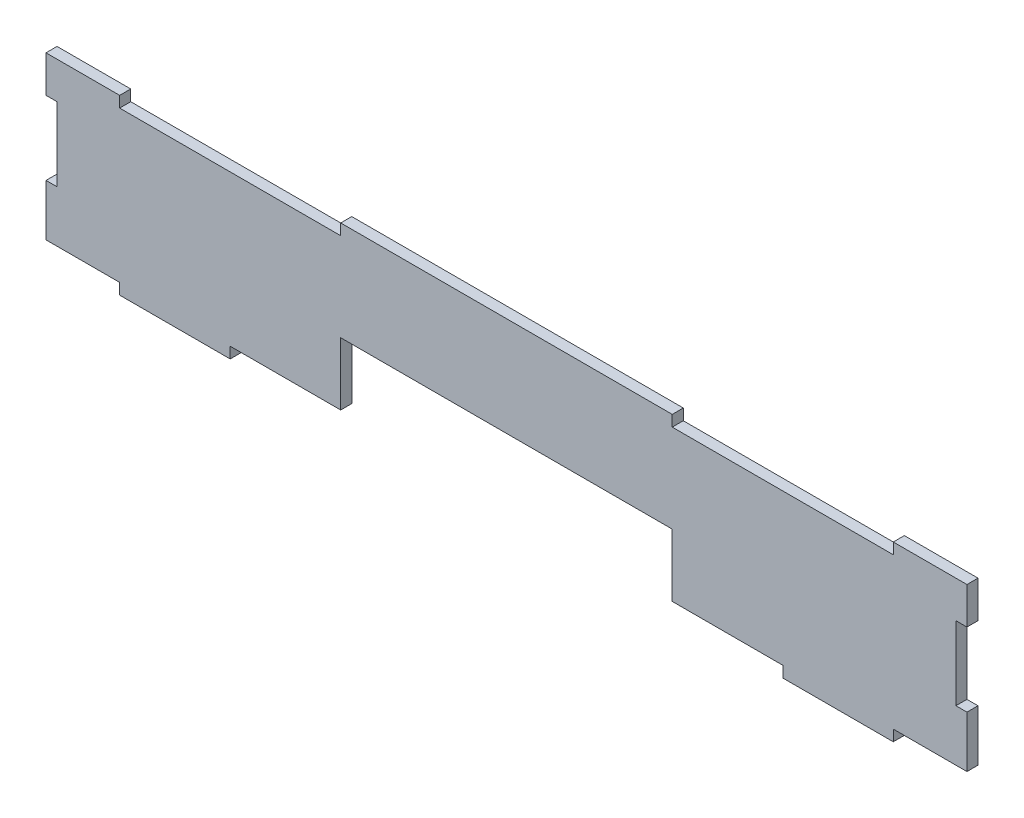
SolidWorks part; units mm, degrees
ref_plane "Front Plane" through (0, 0, 0) normal (0, 0, 1) x (1, 0, 0)
ref_plane "Top Plane" through (0, 0, 0) normal (0, 1, 0) x (1, 0, 0)
ref_plane "Right Plane" through (0, 0, 0) normal (1, 0, 0) x (0, 0, -1)
sketch "Sketch1" plane through (0, 0, 0) normal (0, 0, 1) x (1, 0, 0)
  line L1 (0, 0) -> (250, 0)
  line L2 (0, 0) -> (0, 46.98)
  line L3 (0, 46.98) -> (250, 46.98)
  line L4 (250, 0) -> (250, 46.98)
  dimension "D1" = 250
  dimension "D2" = 46.98
extrude "Boss-Extrude1" add sketch "Sketch1" along normal blind 3
sketch "Sketch2" plane through (0, 0, 3) normal (0, 0, 1) x (1, 0, 0)
  line L0 (250, 0) -> (250, 46.98) construction
  line L1 (250, 36.98) -> (247, 36.98)
  line L2 (250, 36.98) -> (250, 16.98)
  line L3 (250, 16.98) -> (247, 16.98)
  line L4 (247, 36.98) -> (247, 16.98)
  line L5 (0, 46.98) -> (0, 0) construction
  line L6 (0, 36.98) -> (3, 36.98)
  line L7 (0, 36.98) -> (0, 16.98)
  line L8 (0, 16.98) -> (3, 16.98)
  line L9 (3, 36.98) -> (3, 16.98)
  line L10 (250, 46.98) -> (0, 46.98) construction
  dimension "D1" = 3
  dimension "D2" = 3
  dimension "D3" = 20
  dimension "D4" = 20
  dimension "D5" = 10
  dimension "D6" = 10
extrude "Cut-Extrude1" cut sketch "Sketch2" against normal through all
sketch "Sketch3" plane through (0, 0, 3) normal (0, 0, 1) x (1, 0, 0)
  line L0 (250, 46.98) -> (0, 46.98) construction
  line L1 (20, 46.98) -> (80, 46.98)
  line L2 (20, 46.98) -> (20, 43.98)
  line L3 (20, 43.98) -> (80, 43.98)
  line L4 (80, 46.98) -> (80, 43.98)
  line L5 (0, 46.98) -> (0, 36.98) construction
  line L6 (230, 46.98) -> (170, 46.98)
  line L7 (230, 46.98) -> (230, 43.98)
  line L8 (230, 43.98) -> (170, 43.98)
  line L9 (170, 46.98) -> (170, 43.98)
  line L10 (250, 36.98) -> (250, 46.98) construction
  point P12 (250, 41.98)
  dimension "D1" = 60
  dimension "D2" = 60
  dimension "D3" = 20
  dimension "D4" = 20
  dimension "D5" = 3
  dimension "D6" = 3
extrude "Cut-Extrude2" cut sketch "Sketch3" against normal through all
sketch "Sketch4" plane through (0, 0, 0) normal (0, 0, -1) x (-1, 0, 0)
  line L0 (0, 0) -> (-250, 0) construction
  line L1 (-80, 0) -> (-170, 0)
  line L2 (-80, 0) -> (-80, 20)
  line L3 (-80, 20) -> (-170, 20)
  line L4 (-170, 0) -> (-170, 20)
  line L5 (0, 16.98) -> (0, 0) construction
  dimension "D1" = 20
  dimension "D2" = 90
  dimension "D3" = 80
extrude "Cut-Extrude3" cut sketch "Sketch4" against normal up to next
sketch "Sketch6" plane through (0, 0, 3) normal (0, 0, 1) x (1, 0, 0)
  line L1 (0, 0) -> (20, 0)
  line L2 (0, 0) -> (0, 3)
  line L3 (0, 3) -> (20, 3)
  line L4 (20, 0) -> (20, 3)
  line L5 (80, 0) -> (50, 0)
  line L6 (80, 0) -> (80, 3)
  line L7 (80, 3) -> (50, 3)
  line L8 (50, 0) -> (50, 3)
  line L9 (250, 0) -> (230, 0)
  line L10 (250, 0) -> (250, 3)
  line L11 (250, 3) -> (230, 3)
  line L12 (230, 0) -> (230, 3)
  line L13 (170, 0) -> (200, 0)
  line L14 (170, 0) -> (170, 3)
  line L15 (170, 3) -> (200, 3)
  line L16 (200, 0) -> (200, 3)
  dimension "D1" = 3
  dimension "D2" = 3
  dimension "D3" = 20
  dimension "D4" = 30
  dimension "D5" = 3
  dimension "D6" = 3
  dimension "D7" = 20
  dimension "D8" = 30
extrude "Cut-Extrude5" cut sketch "Sketch6" against normal blind 10
